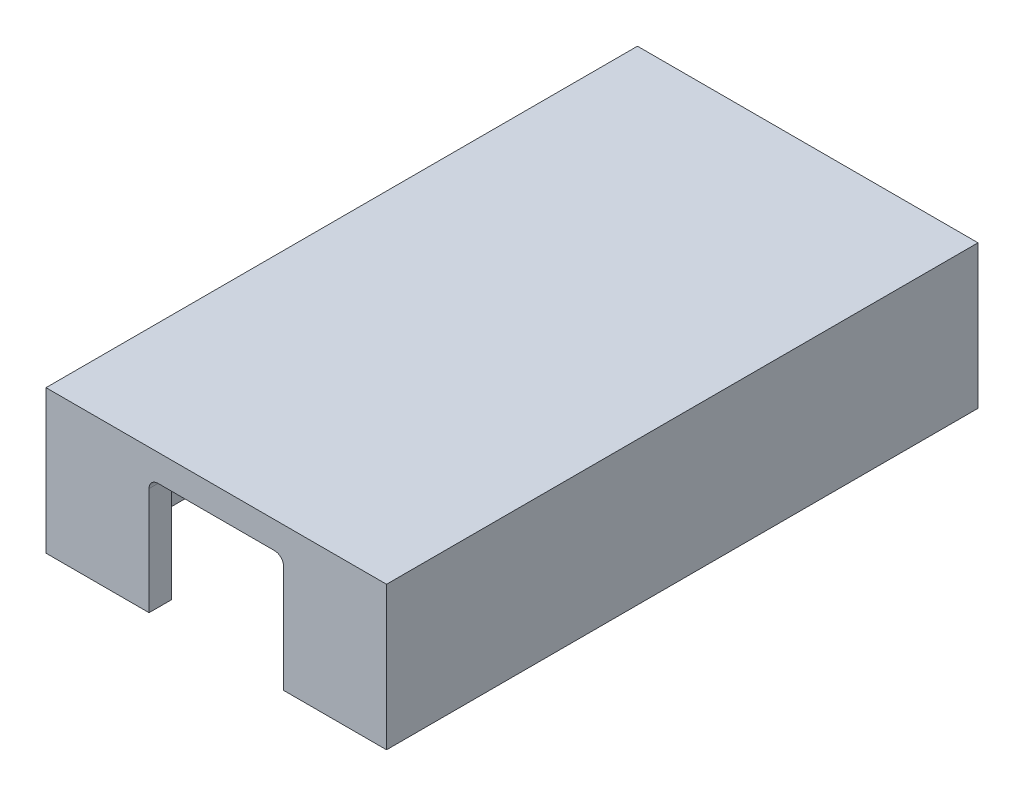
SolidWorks part; units mm, degrees
ref_plane "Front Plane" through (0, 0, 0) normal (0, 0, 1) x (1, 0, 0)
ref_plane "Top Plane" through (0, 0, 0) normal (0, 1, 0) x (1, 0, 0)
ref_plane "Right Plane" through (0, 0, 0) normal (1, 0, 0) x (0, 0, -1)
sketch "Sketch1" plane through (0, 0, 0) normal (0, 1, 0) x (1, 0, 0)
  line L0 (-8.8, 0) -> (8.8, 0) construction
  line L1 (-19, 33) -> (19, 33)
  line L2 (-19, 33) -> (-19, -33)
  line L3 (-19, -33) -> (19, -33)
  line L4 (19, 33) -> (19, -33)
  line L5 (0, -8.8) -> (0, 8.8) construction
  dimension "D1" = 33
  dimension "D2" = 66
  dimension "D3" = 38
  dimension "D4" = 19
extrude "Boss-Extrude1" add sketch "Sketch1" along normal blind 3
sketch "Sketch2" plane through (0, 0, 0) normal (0, 1, 0) x (1, 0, 0)
  line L1 (2.5, 30.5) -> (2.5, 33)
  line L2 (19, 33) -> (2.5, 33)
  line L3 (19, 33) -> (19, -33)
  line L4 (19, -33) -> (7.5, -33)
  line L6 (-19, 33) -> (-19, -33)
  line L8 (16.5, 30.5) -> (2.5, 30.5)
  line L9 (16.5, 30.5) -> (16.5, -30.5)
  line L10 (16.5, -30.5) -> (7.5, -30.5)
  line L11 (-16.5, 30.5) -> (-16.5, -30.5)
  line L12 (-8.5, 30.5) -> (-8.5, 33)
  line L13 (-7.5, -33) -> (-7.5, -30.5)
  line L14 (7.5, -33) -> (7.5, -30.5)
  line L15 (-7.5, -30.5) -> (-16.5, -30.5)
  line L17 (-7.5, -33) -> (-19, -33)
  line L18 (-8.5, 30.5) -> (-16.5, 30.5)
  line L19 (-8.5, 33) -> (-19, 33)
  dimension "D1" = 2.5
  dimension "D2" = 2.5
  dimension "D3" = 2.5
  dimension "D4" = 2.5
  dimension "D5" = 11.5
  dimension "D6" = 11.5
  dimension "D7" = 10.5
  dimension "D8" = 16.5
extrude "Boss-Extrude3" add sketch "Sketch2" against normal blind 13
sketch "Sketch5" plane through (16.5, 0, 0) normal (-1, 0, 0) x (0, 0, 1)
  line L1 (-7.5, -13) -> (7.5, -13)
  line L2 (-7.5, -13) -> (-7.5, -11.5)
  line L3 (-7.5, -11.5) -> (7.5, -11.5)
  line L4 (7.5, -13) -> (7.5, -11.5)
  line L6 (0, -1.65) -> (0, 1.65) construction
  dimension "D1" = 7.5
  dimension "D2" = 15
extrude "Boss-Extrude4" add sketch "Sketch5" along normal blind 1.5
mirror "Mirror1" about plane through (0, 0, 0) normal (1, 0, 0) of "Boss-Extrude4"
fillet "Fillet2" radius 1 2 edges at (15, -13, 0) (-15, -13, 0)
fillet "Fillet3" radius 1 10 edges at (-8.5, 0, -31.75) (-12.5, 0, -30.5) (9.5, 0, -30.5) (16.5, 0, 0) (12, 0, 30.5) (-16.5, 0, 0) (-12, 0, 30.5) (-7.5, 0, 31.75)
